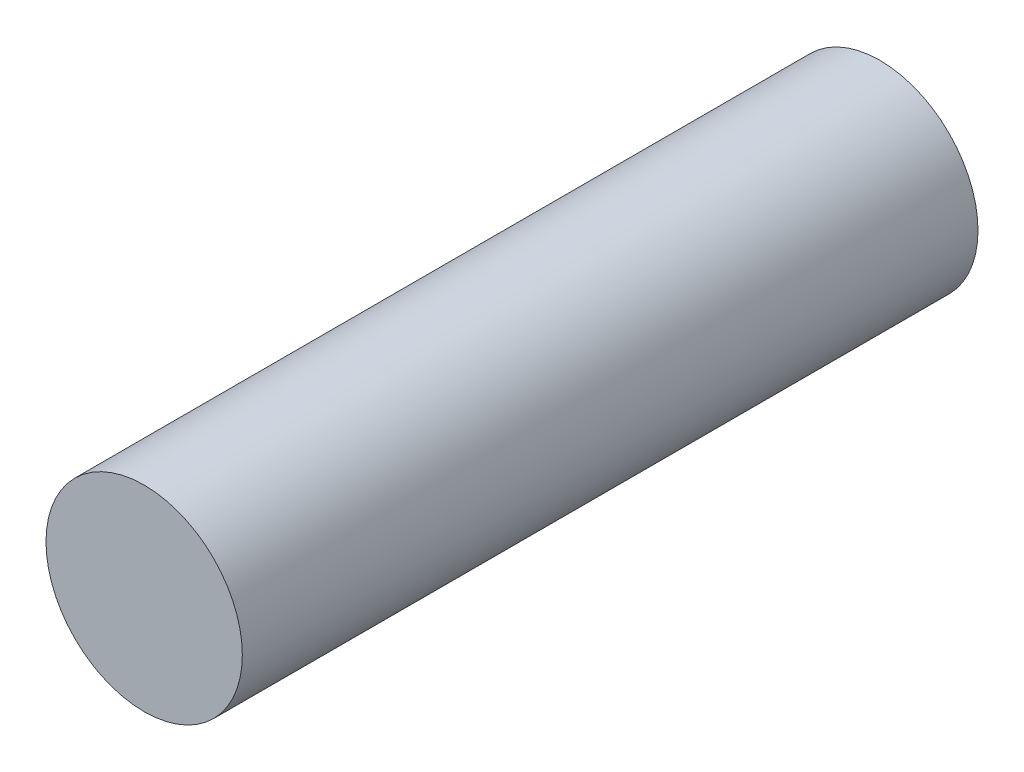
SolidWorks part; units mm, degrees
ref_plane "Front Plane" through (0, 0, 0) normal (0, 0, 1) x (1, 0, 0)
ref_plane "Top Plane" through (0, 0, 0) normal (0, 1, 0) x (1, 0, 0)
ref_plane "Right Plane" through (0, 0, 0) normal (1, 0, 0) x (0, 0, -1)
sketch "Sketch1" plane through (0, 0, 0) normal (0, 0, 1) x (1, 0, 0)
  circle A0 centre (0, 0) radius 50.8381
  dimension "D1" = 101.6762
extrude "Boss-Extrude1" add sketch "Sketch1" along normal blind 381
